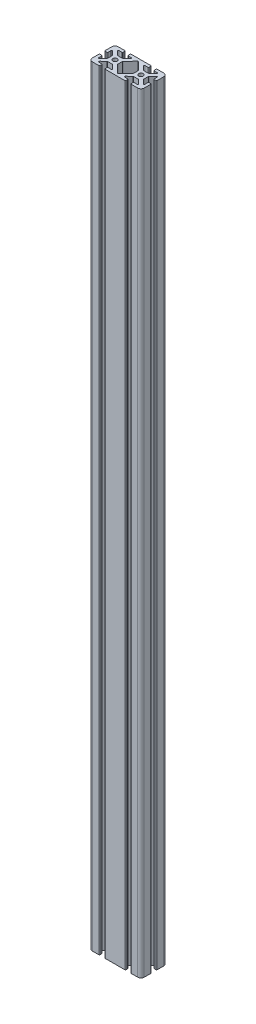
SolidWorks part; units mm, degrees
material "4032-T6"
ref_plane "Front Plane" through (0, 0, 0) normal (0, 0, 1) x (1, 0, 0)
ref_plane "Top Plane" through (0, 0, 0) normal (0, 1, 0) x (1, 0, 0)
ref_plane "Right Plane" through (0, 0, 0) normal (1, 0, 0) x (0, 0, -1)
sketch "Sketch1" plane through (0, 0, 0) normal (0, 1, 0) x (1, 0, 0)
  line L1 (5, 0) -> (75, 0)
  line L2 (0, -5) -> (0, -35)
  line L3 (5, -40) -> (75, -40)
  line L4 (80, -5) -> (80, -35)
  arc A0 (75, -40) -> (80, -35) centre (75, -35) ccw
  arc A1 (80, -5) -> (75, 0) centre (75, -5) ccw
  arc A2 (5, -40) -> (0, -35) centre (5, -35) cw
  arc A3 (0, -5) -> (5, 0) centre (5, -5) cw
  point P7 (80, -40)
  point P10 (80, 0)
  point P15 (0, 0)
  dimension "D3" = 5
  dimension "D1" = 80
  dimension "D2" = 40
extrude "Boss-Extrude1" add sketch "Sketch1" along normal blind 1185.8 contours L3 A0 L4 A1 L1 A3 L2 A2
sketch "Sketch3" plane through (0, 1185.8, 0) normal (0, 1, 0) x (1, 0, 0)
  line L0 (40, -2.5254) -> (40, -32.3671)
  line L1 (0, -5) -> (0, -35) construction
  line L2 (5, 0) -> (75, 0) construction
  circle A0 centre (20, -20) radius 3.4
  dimension "D4" = 6.8
  dimension "D1" = 40
  dimension "D2" = 20
  dimension "D3" = 20
extrude "Cut-Extrude1" cut sketch "Sketch3" against normal through all contours A0
ref_plane "mirro-plane" through (40, 0, 0) normal (1, 0, 0) x (0, 0, -1)
mirror "Mirror3" about plane through (40, 0, 0) normal (1, 0, 0) of "Cut-Extrude1"
ref_plane "sk5mirrorPlane" through (0, 0, 20) normal (0, 0, 1) x (1, 0, 0)
sketch "Sketch7" plane through (0, 0, 0) normal (0, -1, 0) x (-1, 0, 0)
  line L2 (-5, -40) -> (-75, -40) construction
  line L4 (-15.9, -40) -> (-24.1, -40)
  line L8 (-15.9, -40) -> (-15.9, -36.5)
  line L12 (-16.3092, -27.8) -> (-23.6908, -27.8)
  line L23 (-10.5103, -35.5) -> (-14.9, -35.5)
  line L25 (-24.1, -40) -> (-24.1, -36.5)
  line L27 (-15.6082, -28.0868) -> (-9.8093, -33.7868)
  line L31 (-29.4898, -35.5) -> (-25.1, -35.5)
  line L43 (-24.3918, -28.0868) -> (-30.1908, -33.7868)
  arc A0 (-24.3918, -28.0868) -> (-23.6908, -27.8) centre (-23.6908, -28.8) cw
  arc A1 (-16.3092, -27.8) -> (-15.6082, -28.0868) centre (-16.3092, -28.8) cw
  arc A2 (-30.1908, -33.7868) -> (-29.4898, -35.5) centre (-29.4898, -34.5) ccw
  arc A3 (-9.8093, -33.7868) -> (-10.5103, -35.5) centre (-10.5103, -34.5) cw
  arc A4 (-25.1, -35.5) -> (-24.1, -36.5) centre (-25.1, -36.5) cw
  arc A5 (-14.9, -35.5) -> (-15.9, -36.5) centre (-14.9, -36.5) ccw
  point P96 (-24.1, -35.5)
  dimension "D17" = 0
  dimension "D18" = 1
  dimension "D8" = 12.2
extrude "Cut-Extrude2" cut sketch "Sketch7" against normal through all
fillet "Fillet1" radius 1 2 edges at (15.9, 592.9, 40) (24.1, 592.9, 40)
mirror "Mirror8" about plane through (40, 0, 0) normal (1, 0, 0) of "Cut-Extrude2"
fillet "Fillet2" radius 1 1 edges at (55.9, 592.9, 40)
fillet "Fillet3" radius 1 1 edges at (64.1, 592.9, 40)
sketch "Sketch9" plane through (0, 0, 0) normal (0, 1, 0) x (1, 0, 0)
  line L1 (14.8998, -4.5007) -> (10.4505, -4.5007)
  line L3 (24.0998, -3.5) -> (24.1, 0)
  line L4 (15.8998, -3.5008) -> (15.9, 0)
  line L5 (15.9, 0) -> (24.1, 0)
  line L6 (16.1497, -12.2) -> (23.8503, -12.2)
  line L7 (5, 0) -> (75, 0) construction
  line L8 (25.0998, -4.5) -> (29.5503, -4.5)
  line L12 (9.7434, -6.2078) -> (15.4426, -11.9071)
  line L16 (24.5574, -11.9071) -> (30.2574, -6.2071)
  arc A0 (15.8998, -3.5008) -> (14.8998, -4.5007) centre (14.8998, -3.5007) cw
  arc A1 (24.0998, -3.5) -> (25.0998, -4.5) centre (25.0998, -3.5) ccw
  arc A2 (29.5503, -4.5) -> (30.2574, -6.2071) centre (29.5503, -5.5) cw
  arc A3 (24.5574, -11.9071) -> (23.8503, -12.2) centre (23.8503, -11.2) cw
  arc A4 (9.7434, -6.2078) -> (10.4505, -4.5007) centre (10.4505, -5.5007) cw
  arc A5 (15.4426, -11.9071) -> (16.1497, -12.2) centre (16.1497, -11.2) ccw
  dimension "D2" = 1
  dimension "D1" = 0
  dimension "D5" = 12.2
  dimension "D6" = 4.5
extrude "Cut-Extrude3" cut sketch "Sketch9" along normal through all
mirror "Mirror9" about plane through (40, 0, 0) normal (1, 0, 0) of "Cut-Extrude3"
sketch "Sketch10" plane through (0, 0, 0) normal (0, 1, 0) x (1, 0, 0)
  line L0 (4.5, -14.9) -> (4.5, -10.5861)
  line L4 (0, -24.1) -> (3.5, -24.1)
  line L5 (0, -15.9) -> (3.5, -15.9)
  line L8 (12.2, -23.4919) -> (12.2, -16.5081)
  line L10 (0, -5) -> (0, -35) construction
  line L13 (4.5, -29.4139) -> (4.5, -25.1)
  line L25 (11.9205, -24.1853) -> (6.2205, -30.1074)
  line L26 (11.9205, -15.8147) -> (6.2205, -9.8926)
  line L29 (0, -24.1) -> (0, -15.9)
  arc A0 (4.5, -14.9) -> (3.5, -15.9) centre (3.5, -14.9) cw
  arc A1 (3.5, -24.1) -> (4.5, -25.1) centre (3.5, -25.1) cw
  arc A2 (6.2205, -9.8926) -> (4.5, -10.5861) centre (5.5, -10.5861) ccw
  arc A3 (11.9205, -15.8147) -> (12.2, -16.5081) centre (11.2, -16.5081) cw
  arc A4 (11.9205, -24.1853) -> (12.2, -23.4919) centre (11.2, -23.4919) ccw
  arc A5 (4.5, -29.4139) -> (6.2205, -30.1074) centre (5.5, -29.4139) ccw
  dimension "D3" = 1
  dimension "D7" = 12.2
  dimension "D9" = 4.5
  dimension "D17" = 0
extrude "Cut-Extrude4" cut sketch "Sketch10" along normal through all
fillet "Fillet4" radius 1 1 edges at (24.1, 592.9, 0)
fillet "Fillet5" radius 1 1 edges at (64.1, 592.9, 0)
fillet "Fillet6" radius 1 1 edges at (55.9, 592.9, 0)
fillet "Fillet7" radius 1 1 edges at (15.9, 592.9, 0)
fillet "Fillet8" radius 1 1 edges at (0, 592.9, 24.1)
fillet "Fillet9" radius 1 1 edges at (0, 592.9, 15.9)
sketch "Sketch11" plane through (0, 0, 0) normal (0, 1, 0) x (1, 0, 0)
  line L0 (75.5, -29.6797) -> (75.5, -25.1)
  line L1 (80, -5) -> (80, -35) construction
  line L2 (67.5, -16.0953) -> (67.5, -23.9047)
  line L5 (75.5, -14.9) -> (75.5, -10.3203)
  line L7 (80, -24.1) -> (80, -15.9)
  line L8 (80, -5) -> (80, -35) construction
  line L13 (113.5168, -27.8) -> (113.5178, -27.6385)
  line L17 (67.8065, -15.3748) -> (73.8065, -9.5998)
  line L63 (67.8065, -24.6252) -> (73.8065, -30.4002)
  line L66 (76.5, -15.9) -> (80, -15.9)
  line L68 (76.5, -24.1) -> (80, -24.1)
  arc A44 (75.5, -25.1) -> (76.5, -24.1) centre (76.5, -25.1) cw
  arc A45 (75.5, -14.9) -> (76.5, -15.9) centre (76.5, -14.9) ccw
  arc A46 (73.8065, -9.5998) -> (75.5, -10.3203) centre (74.5, -10.3203) cw
  arc A47 (73.8065, -30.4002) -> (75.5, -29.6797) centre (74.5, -29.6797) ccw
  arc A48 (67.8065, -24.6252) -> (67.5, -23.9047) centre (68.5, -23.9047) cw
  arc A49 (67.8065, -15.3748) -> (67.5, -16.0953) centre (68.5, -16.0953) ccw
  dimension "D3" = 1
  dimension "D2" = 4.5
  dimension "D4" = 12.5
ref_plane "offset1" through (60, 0, 0) normal (1, 0, 0) x (0, 0, -1)
mirror "Mirror10" about plane through (40, 0, 0) normal (1, 0, 0) of "Cut-Extrude4"
fillet "Fillet10" radius 1 1 edges at (80, 592.9, 15.9)
fillet "Fillet11" radius 1 1 edges at (80, 592.9, 24.1)
mirror "Mirror11" about plane through (60, 0, 0) normal (1, 0, 0) of "Mirror10"
ref_plane "Plane2" through (20, 0, 0) normal (-1, 0, 0) x (0, 0, 1)
mirror "Mirror12" about plane through (20, 0, 0) normal (-1, 0, 0) of "Cut-Extrude4"
sketch "Sketch12" plane through (0, 0, 0) normal (0, -1, 0) x (-1, 0, 0)
  line L0 (-28.0795, -24.1853) -> (-39.3271, -35.8711)
  line L2 (-51.9226, -24.2109) -> (-40.7702, -35.8689)
  line L4 (-39.2795, -4.1783) -> (-28.0795, -15.8147)
  line L7 (-51.9205, -15.8147) -> (-40.7205, -4.1783)
  line L8 (-27.8, -23.4919) -> (-27.8, -16.5081)
  line L9 (-52.2, -23.5196) -> (-52.2, -16.5081)
  line L10 (-52.2, -23.4919) -> (-52.2, -16.5081) construction
  line L11 (-27.8, -23.4919) -> (-27.8, -16.5081) construction
  arc A0 (-39.2795, -4.1783) -> (-40.7205, -4.1783) centre (-40, -4.8718) ccw
  arc A1 (-39.3271, -35.8711) -> (-40.7702, -35.8689) centre (-40.0476, -35.1776) cw
  arc A2 (-51.9205, -15.8147) -> (-52.2, -16.5081) centre (-51.2, -16.5081) ccw
  arc A3 (-52.2, -23.5196) -> (-51.9226, -24.2109) centre (-51.2, -23.5196) ccw
  arc A4 (-28.0795, -15.8147) -> (-27.8, -16.5081) centre (-28.8, -16.5081) cw
  arc A5 (-27.8, -23.4919) -> (-28.0795, -24.1853) centre (-28.8, -23.4919) cw
  dimension "D3" = 1
  dimension "D4" = 1
  dimension "D1" = 0
  dimension "D2" = 0
extrude "Cut-Extrude5" cut sketch "Sketch12" against normal through all
